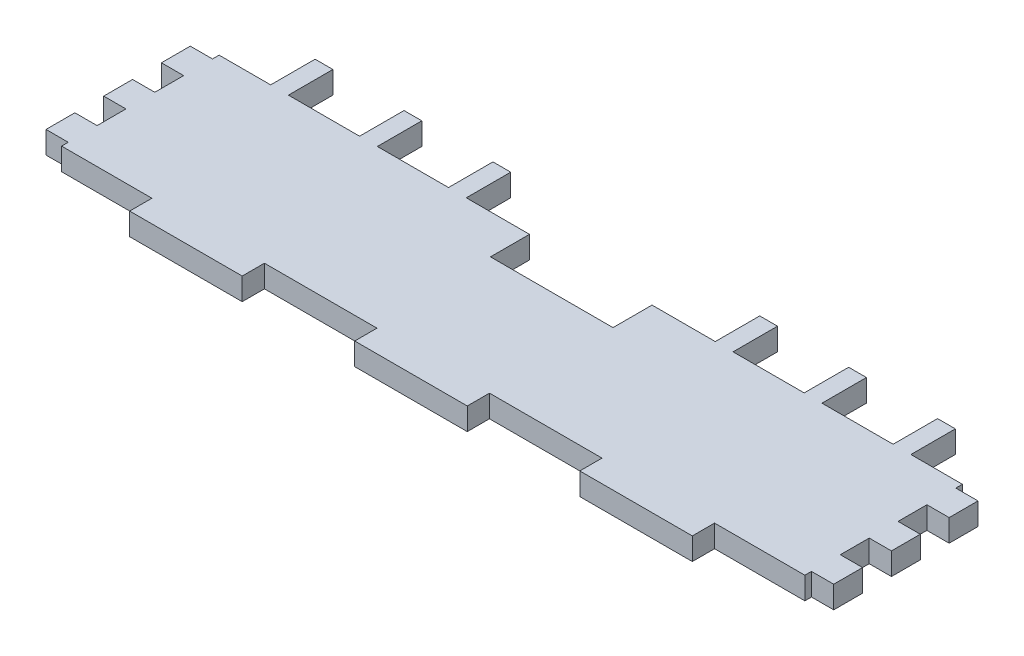
SolidWorks part; units mm, degrees
ref_plane "Front Plane" through (0, 0, 0) normal (0, 0, 1) x (1, 0, 0)
ref_plane "Top Plane" through (0, 0, 0) normal (0, 1, 0) x (1, 0, 0)
ref_plane "Right Plane" through (0, 0, 0) normal (1, 0, 0) x (0, 0, -1)
sketch "Sketch1" plane through (0, 0, 0) normal (0, 1, 0) x (1, 0, 0)
  line L48 (32.1429, 0) -> (32.1429, 6.35)
  line L49 (0, 0) -> (32.1429, 0)
  line L50 (0, 0) -> (0, 6.35)
  line L51 (0, 6.35) -> (32.1429, 6.35)
  line L52 (32.1429, 0) -> (32.1429, 6.35)
  line L53 (0, 0) -> (6.35, 0)
  line L54 (0, 0) -> (0, 8.2429)
  line L55 (0, 8.2429) -> (6.35, 8.2429)
  line L56 (6.35, 0) -> (6.35, 8.2429)
  line L57 (32.1429, 0) -> (64.2857, 0)
  line L58 (64.2857, 0) -> (64.2857, 6.35)
  line L59 (32.1429, 6.35) -> (64.2857, 6.35)
  line L60 (64.2857, 0) -> (64.2857, 6.35)
  line L61 (64.2857, 0) -> (96.4286, 0)
  line L62 (96.4286, 0) -> (96.4286, 6.35)
  line L63 (64.2857, 6.35) -> (96.4286, 6.35)
  line L64 (96.4286, 0) -> (96.4286, 6.35)
  line L65 (96.4286, 0) -> (128.5714, 0)
  line L66 (128.5714, 0) -> (128.5714, 6.35)
  line L67 (96.4286, 6.35) -> (128.5714, 6.35)
  line L72 (128.5714, 0) -> (128.5714, 6.35)
  line L73 (128.5714, 0) -> (160.7143, 0)
  line L74 (160.7143, 0) -> (160.7143, 6.35)
  line L75 (128.5714, 6.35) -> (160.7143, 6.35)
  line L76 (160.7143, 0) -> (160.7143, 6.35)
  line L77 (160.7143, 0) -> (192.8571, 0)
  line L78 (192.8571, 0) -> (192.8571, 6.35)
  line L79 (160.7143, 6.35) -> (192.8571, 6.35)
  line L80 (192.8571, 0) -> (192.8571, 6.35)
  line L81 (192.8571, 0) -> (225, 0)
  line L82 (225, 0) -> (225, 6.35)
  line L83 (192.8571, 6.35) -> (225, 6.35)
  line L84 (0, 8.2429) -> (0, 16.4857)
  line L85 (0, 8.2429) -> (6.35, 8.2429)
  line L86 (6.35, 8.2429) -> (6.35, 16.4857)
  line L87 (0, 16.4857) -> (6.35, 16.4857)
  line L88 (0, 16.4857) -> (0, 24.7286)
  line L89 (0, 16.4857) -> (6.35, 16.4857)
  line L90 (6.35, 16.4857) -> (6.35, 24.7286)
  line L91 (0, 24.7286) -> (6.35, 24.7286)
  line L98 (0, 24.7286) -> (0, 32.9714)
  line L99 (0, 24.7286) -> (6.35, 24.7286)
  line L100 (6.35, 24.7286) -> (6.35, 32.9714)
  line L101 (0, 32.9714) -> (6.35, 32.9714)
  line L102 (0, 32.9714) -> (0, 41.2143)
  line L103 (0, 32.9714) -> (6.35, 32.9714)
  line L104 (6.35, 32.9714) -> (6.35, 41.2143)
  line L105 (0, 41.2143) -> (6.35, 41.2143)
  line L106 (0, 41.2143) -> (0, 49.4571)
  line L107 (0, 41.2143) -> (6.35, 41.2143)
  line L108 (6.35, 41.2143) -> (6.35, 49.4571)
  line L109 (0, 49.4571) -> (6.35, 49.4571)
  line L110 (0, 49.4571) -> (0, 57.7)
  line L111 (0, 49.4571) -> (6.35, 49.4571)
  line L112 (6.35, 49.4571) -> (6.35, 57.7)
  line L113 (0, 57.7) -> (6.35, 57.7)
  line L114 (112.5, 0) -> (112.5, 671.069) construction
  line L115 (-187.856, 28.85) -> (254.8092, 28.85) construction
  line L116 (225, 8.2429) -> (218.65, 8.2429)
  line L117 (218.65, 0) -> (218.65, 8.2429)
  line L118 (225, 0) -> (218.65, 0)
  line L119 (225, 0) -> (225, 8.2429)
  line L120 (225, 49.4571) -> (218.65, 49.4571)
  line L121 (218.65, 49.4571) -> (218.65, 57.7)
  line L122 (225, 57.7) -> (218.65, 57.7)
  line L123 (225, 49.4571) -> (225, 57.7)
  line L124 (225, 41.2143) -> (218.65, 41.2143)
  line L125 (218.65, 41.2143) -> (218.65, 49.4571)
  line L126 (225, 49.4571) -> (218.65, 49.4571)
  line L127 (225, 41.2143) -> (225, 49.4571)
  line L128 (225, 8.2429) -> (218.65, 8.2429)
  line L129 (218.65, 8.2429) -> (218.65, 16.4857)
  line L130 (225, 16.4857) -> (218.65, 16.4857)
  line L131 (225, 8.2429) -> (225, 16.4857)
  line L132 (225, 32.9714) -> (218.65, 32.9714)
  line L133 (218.65, 32.9714) -> (218.65, 41.2143)
  line L134 (225, 41.2143) -> (218.65, 41.2143)
  line L135 (225, 32.9714) -> (225, 41.2143)
  line L136 (225, 24.7286) -> (218.65, 24.7286)
  line L137 (218.65, 24.7286) -> (218.65, 32.9714)
  line L138 (225, 32.9714) -> (218.65, 32.9714)
  line L139 (225, 24.7286) -> (225, 32.9714)
  line L140 (225, 16.4857) -> (218.65, 16.4857)
  line L141 (218.65, 16.4857) -> (218.65, 24.7286)
  line L142 (225, 24.7286) -> (218.65, 24.7286)
  line L143 (225, 16.4857) -> (225, 24.7286)
  line L144 (192.8571, 57.7) -> (225, 57.7)
  line L145 (225, 57.7) -> (225, 51.35)
  line L146 (192.8571, 51.35) -> (225, 51.35)
  line L147 (192.8571, 57.7) -> (192.8571, 51.35)
  line L148 (160.7143, 57.7) -> (192.8571, 57.7)
  line L149 (192.8571, 57.7) -> (192.8571, 51.35)
  line L150 (160.7143, 51.35) -> (192.8571, 51.35)
  line L151 (160.7143, 57.7) -> (160.7143, 51.35)
  line L152 (128.5714, 57.7) -> (160.7143, 57.7)
  line L153 (160.7143, 57.7) -> (160.7143, 51.35)
  line L154 (128.5714, 51.35) -> (160.7143, 51.35)
  line L155 (128.5714, 57.7) -> (128.5714, 51.35)
  line L156 (96.4286, 57.7) -> (128.5714, 57.7)
  line L157 (128.5714, 57.7) -> (128.5714, 51.35)
  line L158 (96.4286, 51.35) -> (128.5714, 51.35)
  line L159 (96.4286, 57.7) -> (96.4286, 51.35)
  line L160 (64.2857, 57.7) -> (96.4286, 57.7)
  line L161 (96.4286, 57.7) -> (96.4286, 51.35)
  line L162 (64.2857, 51.35) -> (96.4286, 51.35)
  line L163 (64.2857, 57.7) -> (64.2857, 51.35)
  line L164 (32.1429, 57.7) -> (64.2857, 57.7)
  line L165 (64.2857, 57.7) -> (64.2857, 51.35)
  line L166 (32.1429, 51.35) -> (64.2857, 51.35)
  line L167 (32.1429, 57.7) -> (32.1429, 51.35)
  line L168 (0, 51.35) -> (32.1429, 51.35)
  line L169 (32.1429, 57.7) -> (32.1429, 51.35)
  line L170 (0, 57.7) -> (32.1429, 57.7)
  line L171 (0, 57.7) -> (0, 51.35)
  point P56 (112.5, 6.35)
  point P58 (6.35, 28.85)
  dimension "D3" = 6.35
  dimension "D4" = 225
  dimension "D5" = 57.7
  dimension "D2" = 7
  dimension "D1" = 7
extrude "Boss-Extrude1" add sketch "Sketch1" along normal blind 6.35 contours L168 L112 L108 L104 L100 L90 L86 L56 L51 L59 L63 L67 L75 L79 L83 L117 L129 L141 L137 L133 L125 L121 L146 L150 L154 L158 L162 L166 | L156 L159 L158 L155 | L67 L62 L65 L66 | L79 L74 L77 L78 | L148 L151 L150 L147 | L164 L167 L166 L163 | L59 L48 L57 L58 | L87 L84 L55 L86 | L101 L98 L91 L100 | L109 L106 L105 L108 | L116 L131 L130 L129 | L136 L139 L132 L137 | L124 L127 L120 L125
sketch "Sketch2" plane through (0, 6.35, 0) normal (0, 1, 0) x (1, 0, 0)
  line L0 (32.1429, 57.7) -> (64.2857, 57.7) construction
  line L1 (6.35, 51.35) -> (218.65, 51.35)
  line L2 (6.35, 51.35) -> (6.35, 57.7)
  line L3 (6.35, 57.7) -> (218.65, 57.7)
  line L4 (218.65, 51.35) -> (218.65, 57.7)
  line L5 (46.46, 64.05) -> (46.46, 57.7)
  line L6 (21.06, 64.05) -> (26.14, 64.05)
  line L7 (21.06, 64.05) -> (21.06, 57.7)
  line L8 (21.06, 57.7) -> (26.14, 57.7)
  line L9 (26.14, 64.05) -> (26.14, 57.7)
  line L10 (46.46, 64.05) -> (51.54, 64.05)
  line L11 (51.54, 64.05) -> (51.54, 57.7)
  line L12 (46.46, 57.7) -> (51.54, 57.7)
  line L13 (71.86, 64.05) -> (71.86, 57.7)
  line L14 (71.86, 64.05) -> (76.94, 64.05)
  line L15 (76.94, 64.05) -> (76.94, 57.7)
  line L16 (71.86, 57.7) -> (76.94, 57.7)
  line L17 (97.26, 64.05) -> (97.26, 57.7)
  line L18 (97.26, 64.05) -> (102.34, 64.05)
  line L19 (102.34, 64.05) -> (102.34, 57.7)
  line L20 (97.26, 57.7) -> (102.34, 57.7)
  line L21 (122.66, 64.05) -> (122.66, 57.7)
  line L22 (122.66, 64.05) -> (127.74, 64.05)
  line L23 (127.74, 64.05) -> (127.74, 57.7)
  line L24 (122.66, 57.7) -> (127.74, 57.7)
  line L25 (148.06, 64.05) -> (148.06, 57.7)
  line L26 (148.06, 64.05) -> (153.14, 64.05)
  line L27 (153.14, 64.05) -> (153.14, 57.7)
  line L28 (148.06, 57.7) -> (153.14, 57.7)
  line L29 (173.46, 64.05) -> (173.46, 57.7)
  line L30 (173.46, 64.05) -> (178.54, 64.05)
  line L31 (178.54, 64.05) -> (178.54, 57.7)
  line L32 (173.46, 57.7) -> (178.54, 57.7)
  line L33 (198.86, 64.05) -> (198.86, 57.7)
  line L34 (198.86, 64.05) -> (203.94, 64.05)
  line L35 (203.94, 64.05) -> (203.94, 57.7)
  line L36 (198.86, 57.7) -> (203.94, 57.7)
  line L45 (224.26, 64.05) -> (224.26, 57.7) [skipped]
  line L46 (224.26, 64.05) -> (229.34, 64.05) [skipped]
  line L47 (229.34, 64.05) -> (229.34, 57.7) [skipped]
  line L48 (224.26, 57.7) -> (229.34, 57.7) [skipped]
  line L49 (249.66, 64.05) -> (249.66, 57.7) [skipped]
  line L50 (249.66, 64.05) -> (254.74, 64.05) [skipped]
  line L51 (254.74, 64.05) -> (254.74, 57.7) [skipped]
  line L52 (249.66, 57.7) -> (254.74, 57.7) [skipped]
  line L53 (112.5, 0) -> (112.5, 77.7946) construction
  line L55 (96.4286, 0) -> (128.5714, 0) construction
  line L56 (112.5, 64.05) -> (122.66, 64.05) construction
  line L57 (112.5, 64.05) -> (102.34, 64.05) construction
  point P44 (112.5, 0)
  point P46 (49, 64.05)
  point P47 (23.6, 64.05)
  dimension "D2" = 5.08
  dimension "D3" = 25.4
  dimension "D4" = 6.35
  dimension "D1" = 10
extrude "Boss-Extrude2" add sketch "Sketch2" against normal up to surface (6.35 mm away) contours L1 L4 L3 L2 | L9 L6 L7 L3 | L11 L10 L5 L3 | L15 L14 L13 L3 | L19 L18 L17 L3 | L35 L34 L33 L3 | L31 L30 L29 L3 | L21 L24 L23 L22 | L27 L28 L25 L26 up to face at (112.5, 0, -28.85)
sketch "Sketch3" plane through (0, 6.35, 0) normal (0, 1, 0) x (1, 0, 0)
  line L1 (112.5, 0) -> (112.5, 57.7) construction
  line L2 (95, 40.2) -> (130, 40.2)
  line L3 (95, 40.2) -> (95, 64.05)
  line L4 (95, 64.05) -> (130, 64.05)
  line L5 (130, 40.2) -> (130, 64.05)
  line L6 (96.4286, 0) -> (128.5714, 0) construction
  line L7 (102.34, 57.7) -> (122.66, 57.7) construction
  line L8 (127.74, 57.7) -> (148.06, 57.7) construction
  line L9 (122.66, 64.05) -> (127.74, 64.05) construction
  point P10 (112.5, 64.05)
  point P11 (130, 53.4826)
  dimension "D1" = 35
  dimension "D2" = 17.5
extrude "Cut-Extrude1" cut sketch "Sketch3" against normal through all
sketch "Sketch4" plane through (0, 6.35, 0) normal (0, 1, 0) x (1, 0, 0)
  line L0 (203.94, 64.05) -> (203.94, 57.7) construction
  line L1 (6.35, 57.7) -> (21.06, 57.7)
  line L2 (6.35, 57.7) -> (6.35, 51.35)
  line L3 (6.35, 51.35) -> (21.06, 51.35)
  line L4 (21.06, 57.7) -> (21.06, 51.35)
  line L5 (26.14, 57.7) -> (46.46, 57.7)
  line L6 (26.14, 57.7) -> (26.14, 51.35)
  line L7 (26.14, 51.35) -> (46.46, 51.35)
  line L8 (46.46, 57.7) -> (46.46, 51.35)
  line L9 (218.65, 57.7) -> (203.94, 57.7)
  line L10 (218.65, 57.7) -> (218.65, 51.35)
  line L11 (218.65, 51.35) -> (203.94, 51.35)
  line L12 (203.94, 57.7) -> (203.94, 51.35)
  line L13 (198.86, 57.7) -> (178.54, 57.7)
  line L14 (198.86, 57.7) -> (198.86, 51.35)
  line L15 (198.86, 51.35) -> (178.54, 51.35)
  line L16 (178.54, 57.7) -> (178.54, 51.35)
  line L17 (203.94, 57.7) -> (218.65, 57.7) construction
  point P20 (178.54, 57.7)
  point P22 (203.94, 57.7)
  point P27 (46.46, 57.7)
  point P29 (21.06, 57.7)
  dimension "D1" = 6.35
extrude "Cut-Extrude2" cut sketch "Sketch4" against normal up to surface (6.35 mm away) up to face at (112.5, 0, -36.9912)
sketch "Sketch5" plane through (0, 6.35, 0) normal (0, 1, 0) x (1, 0, 0)
  line L1 (51.54, 57.7) -> (71.86, 57.7)
  line L2 (51.54, 57.7) -> (51.54, 51.35)
  line L3 (51.54, 51.35) -> (71.86, 51.35)
  line L4 (71.86, 57.7) -> (71.86, 51.35)
  line L5 (76.94, 57.7) -> (95, 57.7)
  line L6 (76.94, 57.7) -> (76.94, 51.35)
  line L7 (76.94, 51.35) -> (95, 51.35)
  line L8 (95, 57.7) -> (95, 51.35)
  line L9 (153.14, 64.05) -> (153.14, 57.7) construction
  line L10 (130, 57.7) -> (148.06, 57.7)
  line L11 (130, 57.7) -> (130, 51.35)
  line L12 (130, 51.35) -> (148.06, 51.35)
  line L13 (148.06, 57.7) -> (148.06, 51.35)
  line L14 (153.14, 57.7) -> (173.46, 57.7)
  line L15 (153.14, 57.7) -> (153.14, 51.35)
  line L16 (153.14, 51.35) -> (173.46, 51.35)
  line L17 (173.46, 57.7) -> (173.46, 51.35)
  line L18 (148.06, 64.05) -> (148.06, 57.7) construction
  line L19 (71.86, 64.05) -> (71.86, 57.7) construction
  line L20 (26.14, 51.35) -> (46.46, 51.35) construction
  line L21 (173.46, 64.05) -> (173.46, 57.7) construction
  point P28 (71.86, 48.4898)
  point P31 (95, 57.7)
extrude "Cut-Extrude3" cut sketch "Sketch5" against normal through all
